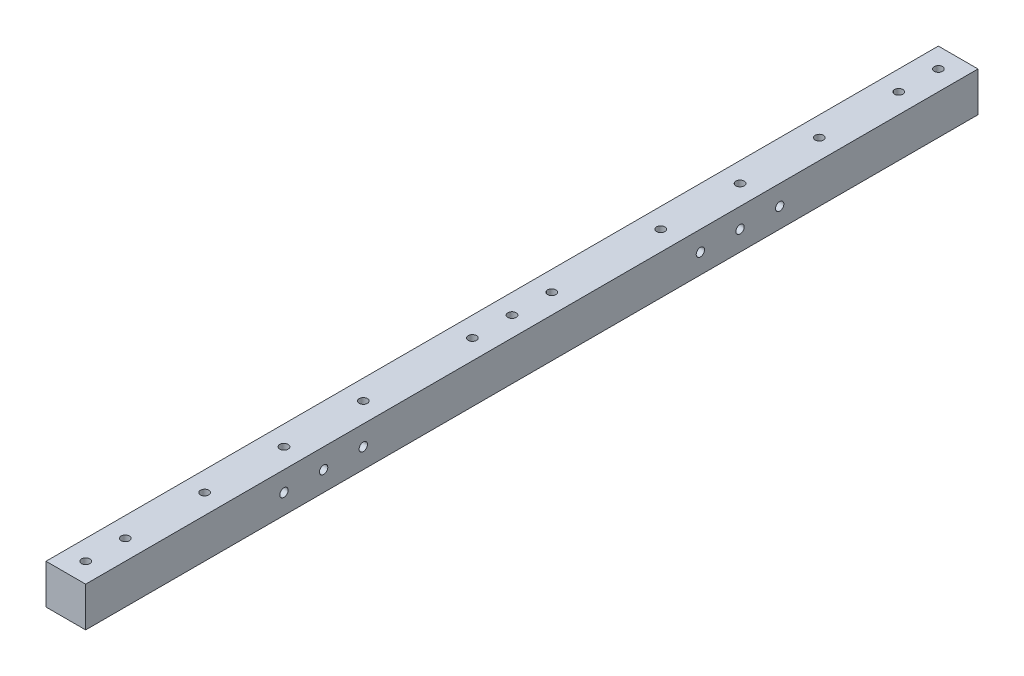
SolidWorks part; units mm, degrees
ref_plane "前视基准面" through (0, 0, 0) normal (0, 0, 1) x (1, 0, 0)
ref_plane "上视基准面" through (0, 0, 0) normal (0, 1, 0) x (1, 0, 0)
ref_plane "右视基准面" through (0, 0, 0) normal (1, 0, 0) x (0, 0, -1)
sketch "草图1" plane through (0, 0, 0) normal (0, 0, 1) x (1, 0, 0)
  line L1 (-10, 10) -> (10, 10)
  line L2 (-10, 10) -> (-10, -10)
  line L3 (-10, -10) -> (10, -10)
  line L4 (10, 10) -> (10, -10)
  line L5 (-10, 10) -> (10, -10) construction
  line L6 (-10, -10) -> (10, 10) construction
  point P0 (0, 0)
  dimension "D1" = 20
  dimension "D2" = 20
extrude "凸台-拉伸1" add sketch "草图1" along normal blind 450
sketch "草图2" plane through (10, 0, 0) normal (1, 0, 0) x (0, 0, -1)
  line L0 (0, -10) -> (0, 10) construction
  line L1 (-450, 10) -> (0, 10) construction
  line L2 (-225, 10) -> (-225, -10) construction
  line L3 (-450, -10) -> (0, -10) construction
  circle A4 centre (-100, 0) radius 2.1
  circle A5 centre (-120, 0) radius 2.1
  circle A6 centre (-140, 0) radius 2.1
  circle A7 centre (-350, 0) radius 2.1
  circle A8 centre (-330, 0) radius 2.1
  circle A9 centre (-310, 0) radius 2.1
  dimension "D7" = 100
  dimension "D8" = 4.2
  dimension "D2" = 10
  dimension "D10" = 20
  dimension "D9" = 3
extrude "切除-拉伸1" cut sketch "草图2" against normal through all
sketch "草图3" plane through (0, 10, 0) normal (0, 1, 0) x (1, 0, 0)
  line L0 (-10, -225) -> (10, -225) construction
  line L1 (-10, -450) -> (-10, 0) construction
  line L2 (10, -450) -> (10, 0) construction
  circle A0 centre (0, -245) radius 2.1
  circle A1 centre (0, -225) radius 2.1
  circle A2 centre (0, -205) radius 2.1
  dimension "D1" = 4.2
  dimension "D5" = 20
  dimension "D2" = 10
  dimension "D3" = 20
  dimension "D4" = 3
extrude "切除-拉伸2" cut sketch "草图3" against normal through all
sketch "草图4" plane through (0, 10, 0) normal (0, 1, 0) x (1, 0, 0)
  line L0 (10, 0) -> (-10, 0) construction
  line L1 (10, -450) -> (10, 0) construction
  line L2 (-10, -225) -> (10, -225) construction
  line L3 (-10, -450) -> (-10, 0) construction
  circle A0 centre (0, -10) radius 2.1
  circle A1 centre (0, -30) radius 2.1
  circle A2 centre (0, -440) radius 2.1
  circle A3 centre (0, -420) radius 2.1
  circle A4 centre (0, -70) radius 2.1
  circle A5 centre (0, -110) radius 2.1
  circle A6 centre (0, -150) radius 2.1
  circle A7 centre (0, -380) radius 2.1
  circle A8 centre (0, -340) radius 2.1
  circle A9 centre (0, -300) radius 2.1
  dimension "D1" = 4.2
  dimension "D5" = 4.2
  dimension "D2" = 20
  dimension "D3" = 10
  dimension "D4" = 10
  dimension "D6" = 4
  dimension "D7" = 40
extrude "切除-拉伸3" cut sketch "草图4" against normal through all
